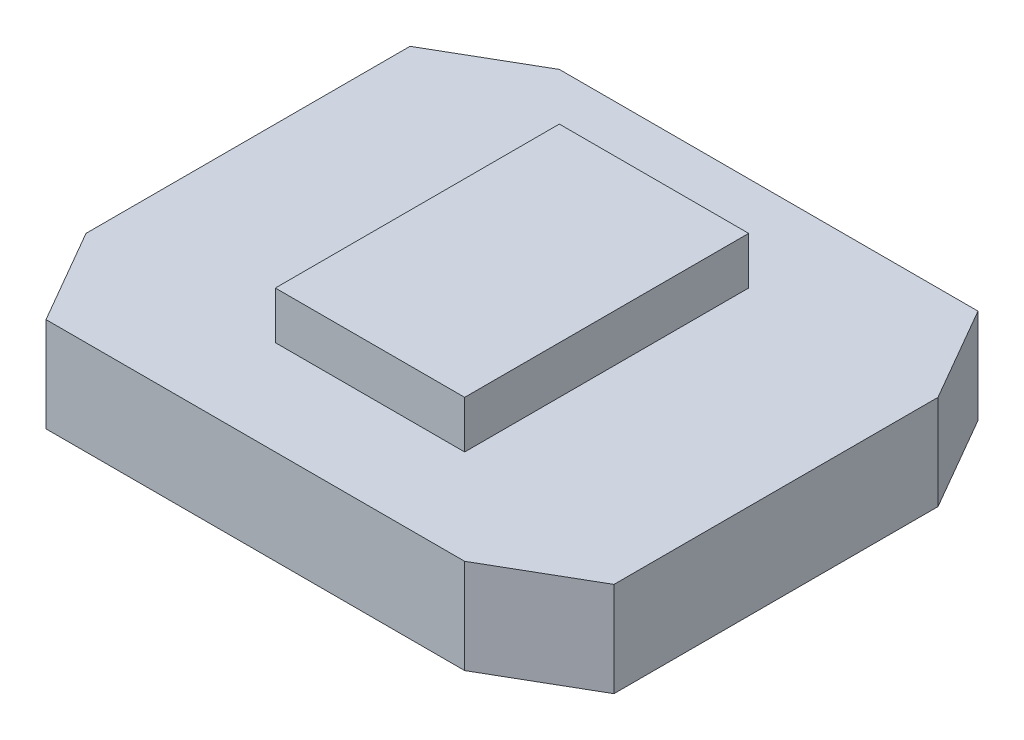
SolidWorks part; units mm, degrees
ref_plane "Front Plane" through (0, 0, 0) normal (0, 0, 1) x (1, 0, 0)
ref_plane "Top Plane" through (0, 0, 0) normal (0, 1, 0) x (1, 0, 0)
ref_plane "Right Plane" through (0, 0, 0) normal (1, 0, 0) x (0, 0, -1)
sketch "Sketch1" plane through (0, 0, 0) normal (0, 1, 0) x (1, 0, 0)
  line L1 (-30, 25) -> (30, 25)
  line L2 (-30, 25) -> (-30, -25)
  line L3 (-30, -25) -> (30, -25)
  line L4 (30, 25) -> (30, -25)
  line L5 (-30, 25) -> (30, -25) construction
  line L6 (-30, -25) -> (30, 25) construction
  point P0 (0, 0)
  dimension "D1" = 50
  dimension "D2" = 60
extrude "Boss-Extrude1" add sketch "Sketch1" along normal blind 15
chamfer "Chamfer1" distance 10 angle 30 4 edges at (-30, 7.5, -25) (30, 7.5, -25) (30, 7.5, 25) (-30, 7.5, 25)
sketch "Sketch2" plane through (0, 15, 0) normal (0, 1, 0) x (1, 0, 0)
  line L1 (-10, 15) -> (10, 15)
  line L2 (-10, 15) -> (-10, -15)
  line L3 (-10, -15) -> (10, -15)
  line L4 (10, 15) -> (10, -15)
  line L5 (-10, 15) -> (10, -15) construction
  line L6 (-10, -15) -> (10, 15) construction
  line L8 (24.2265, 25) -> (-20, 25)
  line L9 (-20, 25) -> (-30, 19.2265)
  line L10 (-30, 19.2265) -> (-30, -15)
  line L11 (-30, -15) -> (-24.2265, -25)
  line L12 (-24.2265, -25) -> (20, -25)
  line L13 (20, -25) -> (30, -19.2265)
  line L14 (30, -19.2265) -> (30, 15)
  line L15 (30, 15) -> (24.2265, 25)
  line L16 (24.2265, 25) -> (-20, 25)
  line L17 (-20, 25) -> (-30, 19.2265)
  line L18 (-30, 19.2265) -> (-30, -15)
  line L19 (-30, -15) -> (-24.2265, -25)
  line L20 (-24.2265, -25) -> (20, -25)
  line L21 (20, -25) -> (30, -19.2265)
  line L22 (30, -19.2265) -> (30, 15)
  line L23 (30, 15) -> (24.2265, 25)
  point P2 (0, 0)
  line M13 (24.2265, 25) -> (-20, 25)
  line M14 (-20, 25) -> (-30, 19.2265)
  line M15 (-30, 19.2265) -> (-30, -15)
  line M16 (-30, -15) -> (-24.2265, -25)
  line M17 (-24.2265, -25) -> (20, -25)
  line M18 (20, -25) -> (30, -19.2265)
  line M19 (30, -19.2265) -> (30, 15)
  line M20 (30, 15) -> (24.2265, 25)
  dimension "D2" = 30
  dimension "D3" = 20
  dimension "D1" = 0
extrude "Cut-Extrude1" cut sketch "Sketch2" against normal blind 5 contours L1 L4 L3 L2 M20 M13 M14 M15 M16 M17 M18 M19
